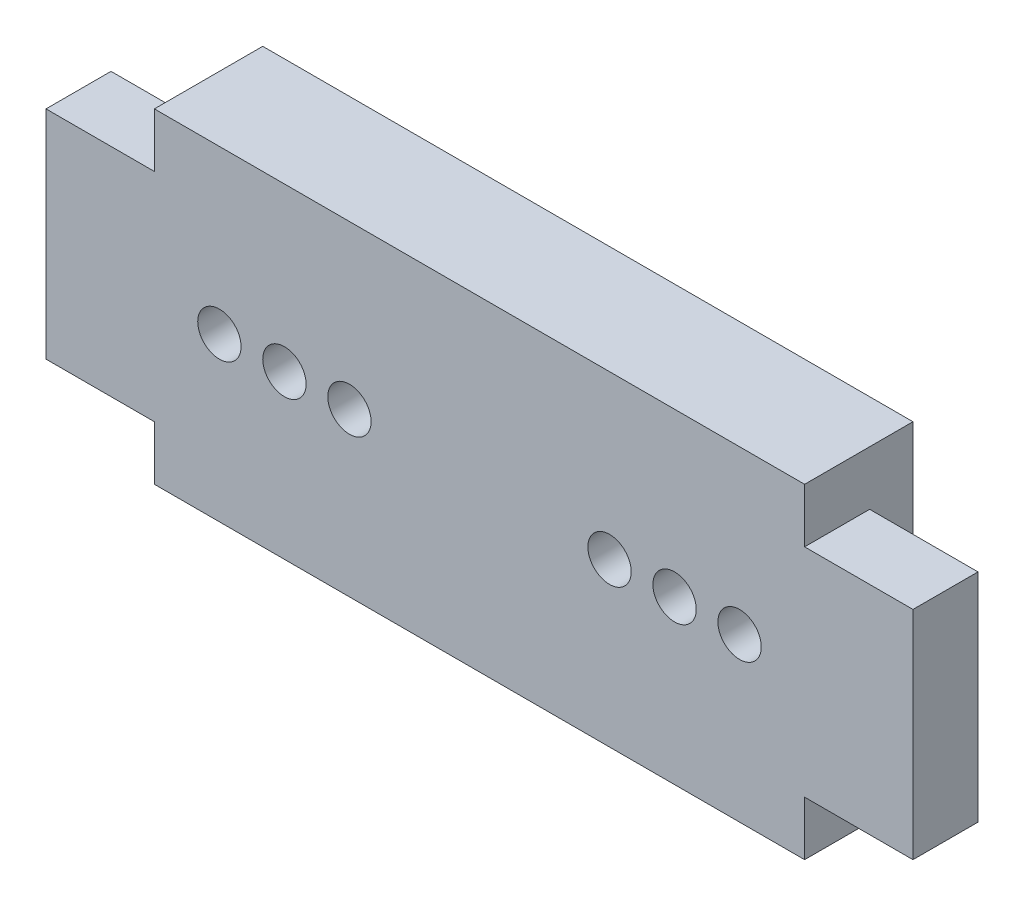
SolidWorks part; units mm, degrees
ref_plane "Front Plane" through (0, 0, 0) normal (0, 0, 1) x (1, 0, 0)
ref_plane "Top Plane" through (0, 0, 0) normal (0, 1, 0) x (1, 0, 0)
ref_plane "Right Plane" through (0, 0, 0) normal (1, 0, 0) x (0, 0, -1)
sketch "Sketch1" plane through (0, 0, 0) normal (0, 1, 0) x (1, 0, 0)
  line L1 (-61.8805, -26.2097) -> (-56.8805, -26.2097)
  line L2 (-61.8805, -26.2097) -> (-61.8805, 28.7903)
  line L3 (-61.8805, 28.7903) -> (-56.8805, 28.7903)
  line L4 (-56.8805, -26.2097) -> (-56.8805, 28.7903)
  line L5 (-56.8805, 28.7903) -> (-26.8805, 28.7903)
  line L6 (-56.8805, 28.7903) -> (-56.8805, 23.7903)
  line L7 (-56.8805, 23.7903) -> (-26.8805, 23.7903)
  line L8 (-26.8805, 28.7903) -> (-26.8805, 23.7903)
  line L9 (-26.8805, 28.7903) -> (-21.8805, 28.7903)
  line L10 (-26.8805, 28.7903) -> (-26.8805, -26.2097)
  line L11 (-26.8805, -26.2097) -> (-21.8805, -26.2097)
  line L12 (-21.8805, 28.7903) -> (-21.8805, -26.2097)
  dimension "D1" = 30
  dimension "D2" = 5
  dimension "D3" = 50
  dimension "D4" = 50
  dimension "D5" = 5
  dimension "D6" = 5
extrude "Boss-Extrude1" add sketch "Sketch1" along normal blind 15 contours L8 L5 L4 L7 | L10 L9 L12 L11
sketch "Sketch3" plane through (0, 0, -28.7903) normal (0, 0, -1) x (-1, 0, 0)
  line L0 (41.8805, 0) -> (41.8805, 15) construction
  line L1 (56.8805, 0) -> (26.8805, 0) construction
  line L2 (56.8805, 15) -> (26.8805, 15) construction
  circle A0 centre (35.8805, 7.5) radius 1
  circle A1 centre (32.8805, 7.5) radius 1
  circle A2 centre (29.8805, 7.5) radius 1
  circle A3 centre (53.8805, 7.5) radius 1
  circle A4 centre (50.8805, 7.5) radius 1
  circle A5 centre (47.8805, 7.5) radius 1
  dimension "D5" = 2
  dimension "D6" = 12
  dimension "D1" = 2
  dimension "D2" = 6
  dimension "D4" = 9
  dimension "D3" = 7.5
extrude "Cut-Extrude2" cut sketch "Sketch3" against normal up to surface (5 mm away) up to face at (-41.8805, 7.5, -23.7903)
sketch "Sketch4" plane through (0, 0, -28.7903) normal (0, 0, -1) x (-1, 0, 0)
  line L2 (56.8805, 0) -> (26.8805, 0) construction
  line L3 (26.8805, 15) -> (26.8805, 0) construction
  circle A0 centre (41.8805, 7.5) radius 2
  dimension "D3" = 4
  dimension "D1" = 7.5
  dimension "D2" = 15
extrude "Cut-Extrude3" cut sketch "Sketch4" against normal blind 1.5
sketch "Sketch5" plane through (0, 0, -23.7903) normal (0, 0, 1) x (1, 0, 0)
  line L0 (-56.8805, 15) -> (-56.8805, 0) construction
  line L1 (-56.8805, 12.5) -> (-61.8805, 12.5)
  line L2 (-56.8805, 12.5) -> (-56.8805, 2.5)
  line L3 (-56.8805, 2.5) -> (-61.8805, 2.5)
  line L4 (-61.8805, 12.5) -> (-61.8805, 2.5)
  line L5 (-56.8805, 15) -> (-26.8805, 15) construction
  line L6 (-56.8805, 0) -> (-26.8805, 0) construction
  line L7 (-41.8805, 15) -> (-41.8805, 0) construction
  line L8 (-26.8805, 2.5) -> (-21.8805, 2.5)
  line L9 (-21.8805, 12.5) -> (-21.8805, 2.5)
  line L10 (-26.8805, 12.5) -> (-21.8805, 12.5)
  line L11 (-26.8805, 12.5) -> (-26.8805, 2.5)
  dimension "D1" = 2.5
  dimension "D2" = 2.5
  dimension "D3" = 5
extrude "Boss-Extrude2" add sketch "Sketch5" against normal blind 3 contours L2 L1 L4 L3 | L8 L9 L10 L11
